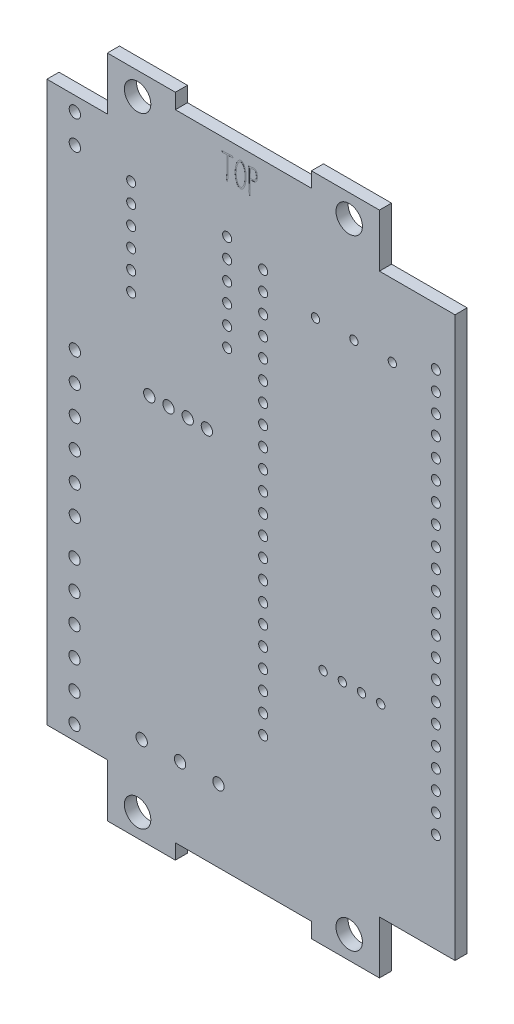
SolidWorks part; units mm, degrees
ref_plane "前视基准面" through (0, 0, 0) normal (0, 0, 1) x (1, 0, 0)
ref_plane "上视基准面" through (0, 0, 0) normal (0, 1, 0) x (1, 0, 0)
ref_plane "右视基准面" through (0, 0, 0) normal (1, 0, 0) x (0, 0, -1)
sketch "草图1" plane through (0, 0, 0) normal (0, 0, 1) x (1, 0, 0)
  line L1 (0, 0) -> (54, 0)
  line L2 (0, 0) -> (0, 88)
  line L3 (0, 88) -> (54, 88)
  line L4 (54, 0) -> (54, 88)
  dimension "D1" = 88
  dimension "D2" = 54
extrude "凸台-拉伸1" add sketch "草图1" along normal blind 1.6
sketch "草图2" plane through (0, 0, 1.6) normal (0, 0, 1) x (1, 0, 0)
  line L0 (26, 88) -> (26, -11.2247) construction
  line L2 (0, 44) -> (77.0225, 44) construction
  line L3 (0, 88) -> (0, 0) construction
  circle A0 centre (12, 85) radius 1.75
  circle A1 centre (40, 85) radius 1.75
  circle A2 centre (12, 3) radius 1.75
  circle A3 centre (40, 3) radius 1.75
  dimension "D1" = 28
  dimension "D2" = 82
  dimension "D3" = 3.5
  dimension "D4" = 12
extrude "切除-拉伸1" cut sketch "草图2" against normal blind 10
sketch "草图3" plane through (0, 0, 0) normal (0, 0, -1) x (-1, 0, 0)
  circle A0 centre (-51.476, 73.476) radius 0.6
  circle A1 centre (-28.616, 73.476) radius 0.6
  dimension "D1" = 1.2
extrude "切除-拉伸2" cut sketch "草图3" against normal blind 10
pattern_linear "阵列(线性)1" count 22 spacing 2.54 along (0, -1, 0) of "切除-拉伸2"
sketch "草图4" plane through (0, 0, 0) normal (0, 0, -1) x (-1, 0, 0)
  circle A0 centre (-3.7, 51.815) radius 0.75
  circle A1 centre (-3.6518, 27.955) radius 0.75
  dimension "D1" = 1.5
extrude "切除-拉伸3" cut sketch "草图4" against normal blind 10
pattern_linear "阵列(线性)2" count 6 spacing 3.81 along (0, -1, 0) of "切除-拉伸3"
sketch "草图5" plane through (0, 0, 0) normal (0, 0, -1) x (-1, 0, 0)
  circle A0 centre (-3.7, 79.095) radius 0.75
  dimension "D1" = 1.5
extrude "切除-拉伸4" cut sketch "草图5" against normal blind 10
pattern_linear "阵列(线性)3" count 2 spacing 3.81 along (0, -1, 0) of "切除-拉伸4"
sketch "草图6" plane through (0, 0, 1.6) normal (0, 0, 1) x (1, 0, 0)
  circle A0 centre (11.15, 74.85) radius 0.6
  circle A1 centre (23.85, 74.85) radius 0.6
  dimension "D1" = 1.2
extrude "切除-拉伸5" cut sketch "草图6" against normal blind 10
pattern_linear "阵列(线性)4" count 6 spacing 2.54 along (0, -1, 0) of "切除-拉伸5"
sketch "草图7" plane through (0, 0, 1.6) normal (0, 0, 1) x (1, 0, 0)
  line L1 (0, 88) -> (8, 88)
  line L2 (0, 88) -> (0, 81)
  line L3 (0, 81) -> (8, 81)
  line L4 (8, 88) -> (8, 81)
  line L5 (54, 88) -> (44, 88)
  line L6 (54, 88) -> (54, 81)
  line L7 (54, 81) -> (44, 81)
  line L8 (44, 88) -> (44, 81)
  line L9 (0, 0) -> (8, 0)
  line L10 (0, 0) -> (0, 7)
  line L11 (0, 7) -> (8, 7)
  line L12 (8, 0) -> (8, 7)
  line L13 (54, 0) -> (44, 0)
  line L14 (54, 0) -> (54, 7)
  line L15 (54, 7) -> (44, 7)
  line L16 (44, 0) -> (44, 7)
  dimension "D1" = 8
  dimension "D2" = 7
  dimension "D3" = 10
  dimension "D4" = 7
  dimension "D5" = 8
  dimension "D6" = 7
  dimension "D7" = 10
  dimension "D8" = 7
extrude "切除-拉伸6" cut sketch "草图7" against normal blind 10
sketch "草图8" plane through (0, 0, 0) normal (0, 0, -1) x (-1, 0, 0)
  circle A0 centre (-45.7, 71.4) radius 0.55
  circle A1 centre (-40.62, 71.4) radius 0.55
  circle A2 centre (-35.54, 71.4) radius 0.55
  circle A3 centre (-44.17, 31.5) radius 0.55
  circle A4 centre (-41.63, 31.5) radius 0.55
  circle A5 centre (-39.09, 31.5) radius 0.55
  circle A6 centre (-36.55, 31.5) radius 0.55
  dimension "D1" = 1.1
extrude "切除-拉伸7" cut sketch "草图8" against normal blind 10
sketch "草图9" plane through (0, 0, 1.6) normal (0, 0, 1) x (1, 0, 0)
  circle A0 centre (13.55, 51.5) radius 0.75
  circle A1 centre (16.09, 51.5) radius 0.75
  circle A2 centre (18.63, 51.5) radius 0.75
  circle A3 centre (21.17, 51.5) radius 0.75
  circle A4 centre (12.54, 11.6) radius 0.75
  circle A5 centre (17.62, 11.6) radius 0.75
  circle A6 centre (22.7, 11.6) radius 0.75
  dimension "D1" = 1.5
extrude "切除-拉伸8" cut sketch "草图9" against normal blind 10
sketch "草图10" plane through (0, 0, 0) normal (0, -1, 0) x (1, 0, 0)
  line L0 (8, 1.6) -> (44, 1.6) construction
  line L1 (17, 1.6) -> (35, 1.6)
  line L2 (17, 1.6) -> (17, 0)
  line L3 (17, 0) -> (35, 0)
  line L4 (35, 1.6) -> (35, 0)
  line L5 (8, 0) -> (44, 0) construction
  line L6 (8, 0) -> (8, 1.6) construction
  line L7 (44, 0) -> (44, 1.6) construction
  dimension "D1" = 9
  dimension "D2" = 9
extrude "切除-拉伸9" cut sketch "草图10" against normal blind 2
ref_plane "基准面1" through (0, 44, 0) normal (0, -1, 0) x (-1, 0, 0)
mirror "镜向1" about plane through (0, 44, 0) normal (0, -1, 0) of "切除-拉伸9"
sketch "草图11" plane through (0, 0, 1.6) normal (0, 0, 1) x (1, 0, 0)
  text T0 "TOP"
extrude "切除-拉伸10" cut sketch "草图11" against normal blind 0.01
